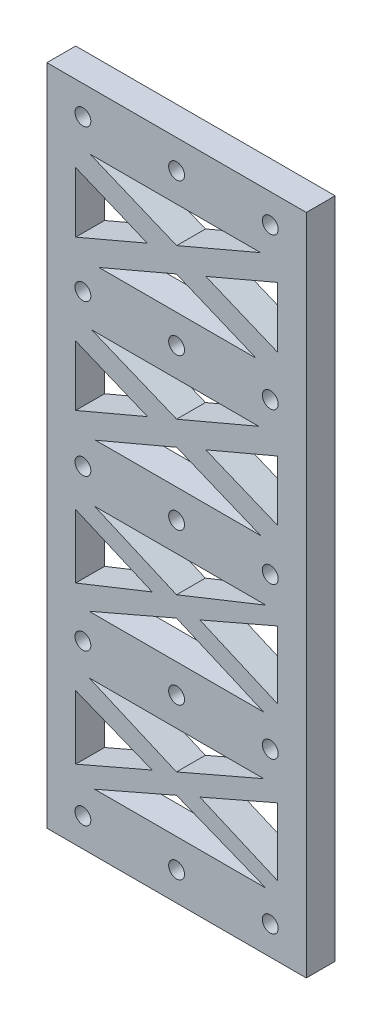
SolidWorks part; units mm, degrees
ref_plane "前视基准面" through (0, 0, 0) normal (0, 0, 1) x (1, 0, 0)
ref_plane "上视基准面" through (0, 0, 0) normal (0, 1, 0) x (1, 0, 0)
ref_plane "右视基准面" through (0, 0, 0) normal (1, 0, 0) x (0, 0, -1)
sketch "草图1" plane through (0, 0, 0) normal (0, 0, 1) x (1, 0, 0)
  line L1 (-36, 50) -> (36, 50)
  line L2 (-36, 50) -> (-36, -50)
  line L3 (-36, -50) -> (36, -50)
  line L4 (36, 50) -> (36, -50)
  line L5 (-36, 50) -> (36, -50) construction
  line L6 (-36, -50) -> (36, 50) construction
  point P0 (0, 0)
  dimension "D1" = 100
  dimension "D2" = 72
extrude "凸台-拉伸1" add sketch "草图1" along normal blind 8
sketch "草图2" plane through (0, 0, 8) normal (0, 0, 1) x (1, 0, 0)
  line L0 (36, -50) -> (36, 50) construction
  line L1 (-28, 34) -> (28, 34)
  line L2 (-28, 34) -> (-28, 8)
  line L3 (-28, 8) -> (28, 8)
  line L4 (28, 34) -> (28, 8)
  line L5 (-28, -8) -> (28, -8)
  line L6 (-28, -8) -> (-28, -34)
  line L7 (-28, -34) -> (28, -34)
  line L8 (28, -8) -> (28, -34)
  line L9 (-36, 50) -> (-36, -50) construction
  line L10 (0, 50) -> (0, -50) construction
  line L11 (36, 50) -> (-36, 50) construction
  line L12 (-36, -50) -> (36, -50) construction
  line L13 (-36, 0) -> (36, 0) construction
  circle A0 centre (-26, -42) radius 2.2
  circle A1 centre (0, -42) radius 2.2
  circle A2 centre (26, -42) radius 2.2
  circle A3 centre (26, 42) radius 2.2
  circle A4 centre (0, 42) radius 2.2
  circle A5 centre (-26, 42) radius 2.2
  circle A6 centre (-26, 0) radius 2.2
  circle A7 centre (0, 0) radius 2.2
  circle A8 centre (26, 0) radius 2.2
  dimension "D6" = 4.4
  dimension "D7" = 4.4
  dimension "D8" = 4.4
  dimension "D9" = 4.4
  dimension "D10" = 4.4
  dimension "D11" = 4.4
  dimension "D1" = 8
  dimension "D2" = 8
  dimension "D3" = 8
  dimension "D4" = 26
  dimension "D5" = 26
  dimension "D12" = 8
  dimension "D13" = 8
  dimension "D14" = 8
  dimension "D15" = 8
  dimension "D16" = 8
  dimension "D17" = 8
  dimension "D18" = 26
  dimension "D19" = 26
extrude "切除-拉伸1" cut sketch "草图2" against normal up to next
sketch "草图3" plane through (0, 0, 8) normal (0, 0, 1) x (1, 0, 0)
  line L0 (-28, 30.6012) -> (-6.7687, 21.4072)
  line L1 (-28, 34) -> (-28, 8) construction
  line L2 (-28, 8) -> (28, 8) construction
  line L3 (-22.7461, 34) -> (-0.0166, 24.1027)
  line L4 (28, 34) -> (-28, 34) construction
  line L5 (28, 8) -> (28, 34) construction
  line L7 (-24.2882, 8) -> (-0.0258, 18.4873)
  line L8 (-28, 30.6012) -> (-28, 34)
  line L9 (-28, 34) -> (-22.7461, 34)
  line L11 (28, 34) -> (28, 30.6012)
  line L12 (28, 11.9032) -> (28, 8)
  line L13 (28, 8) -> (24.1918, 8)
  line L15 (-28, 8) -> (-24.2882, 8)
  line L16 (0, 50) -> (0, 24.1093) construction
  line L17 (36, 50) -> (-36, 50) construction
  line L18 (-36, -50) -> (36, -50) construction
  line L22 (24.7762, 34) -> (-0.0166, 24.1027)
  line L24 (24.7762, 34) -> (28, 34)
  line L25 (6.4506, 21.2866) -> (28, 11.9032)
  line L26 (-6.7687, 21.4072) -> (-28, 12.9316)
  line L27 (-0.0258, 18.4873) -> (24.1918, 8)
  line L28 (6.4506, 21.2866) -> (28, 30.6012)
  line L29 (-28, 12.9316) -> (-28, 8)
  line L30 (0, 18.4761) -> (0, -50) construction
  line L31 (-36, 0) -> (36, 0) construction
  line L32 (-36, 50) -> (-36, -50) construction
  line L33 (36, -50) -> (36, 50) construction
  line L34 (-28, -8) -> (-24.2882, -8)
  line L35 (-28, -12.9316) -> (-28, -8)
  line L36 (-6.7687, -21.4072) -> (-28, -12.9316)
  line L37 (-28, -30.6012) -> (-6.7687, -21.4072)
  line L38 (-28, -30.6012) -> (-28, -34)
  line L39 (-28, -34) -> (-22.7461, -34)
  line L40 (-22.7461, -34) -> (-0.0166, -24.1027)
  line L41 (24.7762, -34) -> (-0.0166, -24.1027)
  line L42 (24.7762, -34) -> (28, -34)
  line L43 (28, -34) -> (28, -30.6012)
  line L44 (6.4506, -21.2866) -> (28, -30.6012)
  line L45 (6.4506, -21.2866) -> (28, -11.9032)
  line L46 (28, -11.9032) -> (28, -8)
  line L47 (28, -8) -> (24.1918, -8)
  line L48 (-0.0258, -18.4873) -> (24.1918, -8)
  line L49 (-24.2882, -8) -> (-0.0258, -18.4873)
extrude "凸台-拉伸2" add sketch "草图3" against normal blind 8
sketch "草图4" plane through (0, 0, 8) normal (0, 0, 1) x (1, 0, 0)
  line L1 (-36, 50) -> (36, 50)
  line L2 (-36, 50) -> (-36, 134)
  line L3 (-36, 134) -> (36, 134)
  line L4 (36, 50) -> (36, 134)
  dimension "D1" = 72
  dimension "D2" = 84
extrude "凸台-拉伸3" add sketch "草图4" against normal blind 8
sketch "草图5" plane through (0, 0, 8) normal (0, 0, 1) x (1, 0, 0)
  line L0 (0, 134) -> (0, 45.4216) construction
  line L1 (36, 134) -> (-36, 134) construction
  line L2 (-36, 134) -> (-36, -50) construction
  line L3 (-28, 118) -> (28, 118)
  line L4 (-28, 118) -> (-28, 92)
  line L5 (-28, 92) -> (28, 92)
  line L6 (28, 118) -> (28, 92)
  line L7 (-28, 118) -> (28, 92) construction
  line L8 (-28, 92) -> (28, 118) construction
  line L9 (-28, 76) -> (28, 76)
  line L10 (-28, 76) -> (-28, 50)
  line L11 (-28, 50) -> (28, 50)
  line L12 (28, 76) -> (28, 50)
  line L13 (-28, 76) -> (28, 50) construction
  line L14 (-28, 50) -> (28, 76) construction
  line L15 (0, 84) -> (56.4662, 84) construction
  line L16 (0, 126) -> (40.8298, 126) construction
  line L17 (0, 126) -> (-31.0914, 126) construction
  line L19 (0, 84) -> (-37.4457, 84) construction
  circle A0 centre (0, 84) radius 2.2
  circle A1 centre (0, 126) radius 2.2
  circle A2 centre (0, 42) radius 2.2 construction
  circle A3 centre (26, 126) radius 2.2
  circle A4 centre (-26, 126) radius 2.2
  circle A6 centre (-26, 84) radius 2.2
  circle A7 centre (26, 84) radius 2.2
  point P9 (0, 63)
  point P11 (0, 105)
  dimension "D1" = 4.4
  dimension "D2" = 4.4
  dimension "D10" = 42
  dimension "D11" = 4.4
  dimension "D12" = 26
  dimension "D13" = 4.4
  dimension "D14" = 26
  dimension "D15" = 26
  dimension "D16" = 4.4
  dimension "D17" = 4.4
  dimension "D18" = 26
  dimension "D3" = 8
  dimension "D4" = 8
  dimension "D5" = 8
  dimension "D6" = 8
  dimension "D7" = 8
  dimension "D8" = 8
  dimension "D9" = 8
extrude "切除-拉伸2" cut sketch "草图5" against normal blind 8
sketch "草图6" plane through (0, 0, 8) normal (0, 0, 1) x (1, 0, 0)
  line L0 (0, 134) -> (0, 45.6723) construction
  line L1 (36, 134) -> (-36, 134) construction
  line L2 (-23.9749, 118) -> (0.0195, 108.0359)
  line L3 (28, 118) -> (-28, 118) construction
  line L4 (28, 92) -> (28, 118) construction
  line L5 (-28, 112.7922) -> (-8.1432, 104.5463)
  line L6 (-28, 118) -> (-28, 92) construction
  line L7 (-28, 92) -> (28, 92) construction
  line L8 (-28, 96.0575) -> (-8.1432, 104.5463)
  line L9 (28, 113.1796) -> (8.1095, 104.6764)
  line L10 (-28, 112.7922) -> (-28, 118)
  line L11 (-28, 118) -> (-23.9749, 118)
  line L12 (23.3272, 118) -> (28, 118)
  line L13 (28, 118) -> (28, 113.1796)
  line L14 (28, 96.4165) -> (28, 92)
  line L15 (28, 92) -> (22.0694, 92)
  line L16 (-21.5427, 92) -> (-28, 92)
  line L17 (-28, 92) -> (-28, 96.0575)
  line L18 (0.0195, 108.0359) -> (23.3272, 118)
  line L19 (8.1095, 104.6764) -> (28, 96.4165)
  line L20 (-0.0532, 101.1868) -> (-21.5427, 92)
  line L21 (-0.0532, 101.1868) -> (22.0694, 92)
  line L22 (-23.5477, 76) -> (0.0122, 66.3148)
  line L23 (28, 76) -> (-28, 76) construction
  line L24 (28, 50) -> (28, 76) construction
  line L25 (-28, 71.0999) -> (-8.0397, 62.8945)
  line L26 (-28, 76) -> (-28, 50) construction
  line L27 (-28, 50) -> (28, 50) construction
  line L28 (22.8123, 76) -> (0.0122, 66.3148)
  line L29 (28, 71.4519) -> (8.0897, 62.9943)
  line L30 (-28, 71.0999) -> (-28, 76)
  line L31 (-28, 76) -> (-23.5477, 76)
  line L32 (22.8123, 76) -> (28, 76)
  line L33 (28, 76) -> (28, 71.4519)
  line L34 (28, 54.8094) -> (28, 50)
  line L35 (28, 50) -> (23.3272, 50)
  line L36 (-28, 54.4156) -> (-28, 50)
  line L37 (-28, 50) -> (-22.5004, 50)
  line L38 (-8.0397, 62.8945) -> (-28, 54.4156)
  line L39 (8.0897, 62.9943) -> (28, 54.8094)
  line L40 (0.0379, 59.5739) -> (-22.5004, 50)
  line L41 (0.0379, 59.5739) -> (23.3272, 50)
extrude "凸台-拉伸4" add sketch "草图6" against normal blind 8
